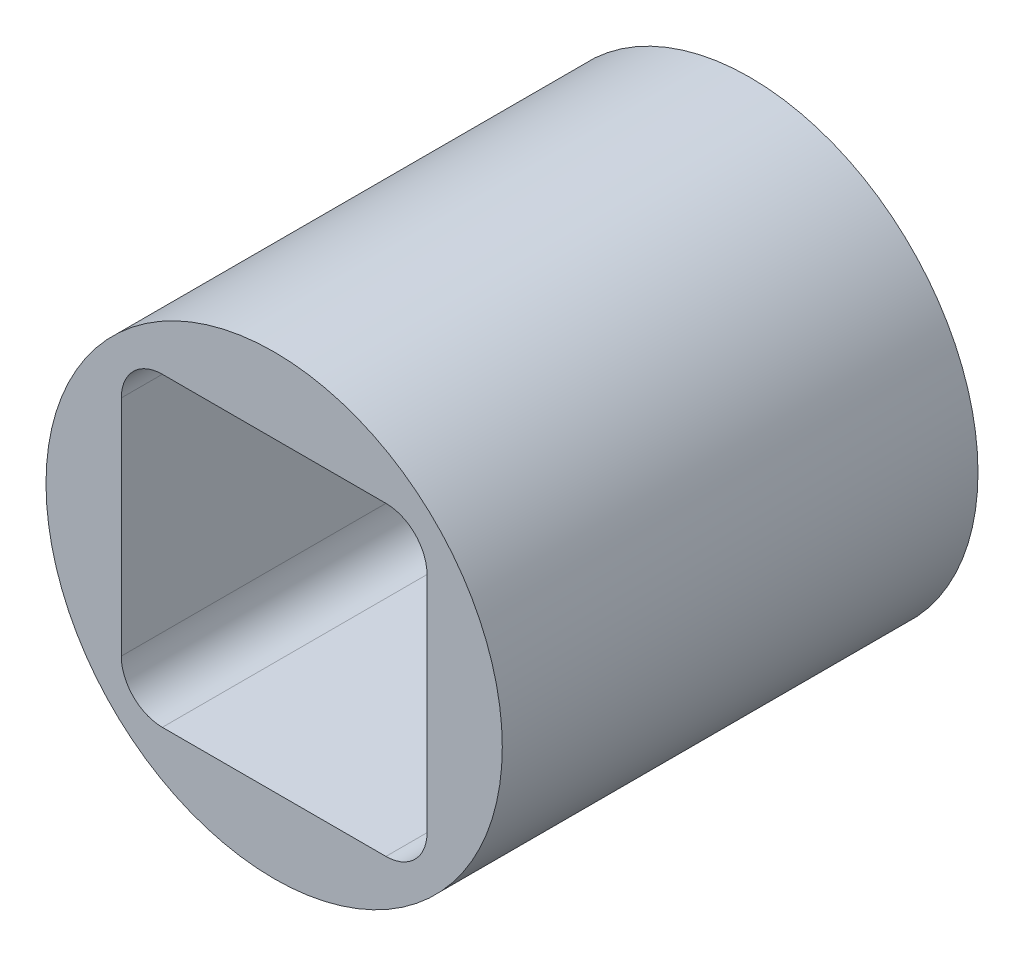
SolidWorks part; units mm, degrees
ref_plane "Front Plane" through (0, 0, 0) normal (0, 0, 1) x (1, 0, 0)
ref_plane "Top Plane" through (0, 0, 0) normal (0, 1, 0) x (1, 0, 0)
ref_plane "Right Plane" through (0, 0, 0) normal (1, 0, 0) x (0, 0, -1)
sketch "Sketch1" plane through (0, 0, 0) normal (0, 0, 1) x (1, 0, 0)
  line L1 (-1.6, 1.6) -> (1.6, 1.6)
  line L2 (-1.6, 1.6) -> (-1.6, -1.6)
  line L3 (-1.6, -1.6) -> (1.6, -1.6)
  line L4 (1.6, 1.6) -> (1.6, -1.6)
  line L5 (-1.6, 1.6) -> (1.6, -1.6) construction
  line L6 (-1.6, -1.6) -> (1.6, 1.6) construction
  circle A0 centre (0, 0) radius 2.3876
  dimension "D1" = 4.7752
  dimension "D2" = 3.2
  dimension "D3" = 3.2
extrude "Boss-Extrude1" add sketch "Sketch1" along normal blind 4.9784 contours A0 L1 L4 L3 L2
fillet "Fillet1" radius 0.43 4 edges at (-1.6, -1.6, 2.4892) (1.6, -1.6, 2.4892) (1.6, 1.6, 2.4892) (-1.6, 1.6, 2.4892)
